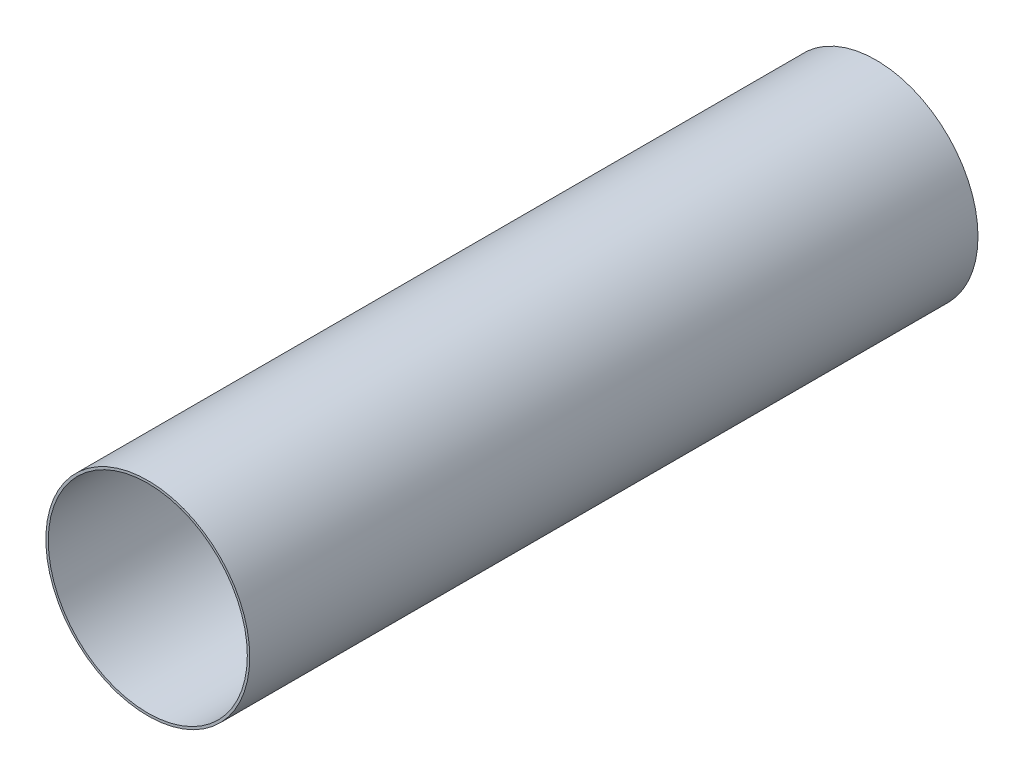
SolidWorks part; units mm, degrees
ref_plane "Alzado" through (0, 0, 0) normal (0, 0, 1) x (1, 0, 0)
ref_plane "Planta" through (0, 0, 0) normal (0, 1, 0) x (1, 0, 0)
ref_plane "Vista lateral" through (0, 0, 0) normal (1, 0, 0) x (0, 0, -1)
sketch "Croquis1" plane through (0, 0, 0) normal (0, 0, 1) x (1, 0, 0)
  circle A0 centre (0, 0) radius 2.05
  circle A1 centre (0, 0) radius 2.1
  dimension "D1" = 4.1
  dimension "D2" = 4.2
extrude "Saliente-Extruir1" add sketch "Croquis1" along normal blind 15 contours A1 A0
equation "\"k\"= 25.884"
equation "\"A_ALETA\"= ( ( ( tan ( \"ANG_ALETA\" ) ) * \"L_ALETA\" ) + \"A_BASE\" - ( \"GAP_ALETAS\" / 2 ) )"
equation "\"A_BASE\"= ( \"L_DIE\" - \"E_CAJA\" )"
equation "\"L_ALETA\"=90.000000"
equation "\"TAU_ALETA\"= ( \"L_ALETA\" / ( log ( ( \"A_ALETA\" ) + 1 ) ) )"
equation "\"E_ALETA\"=5.000000"
equation "\"R_SONDA\"= 2.05"
equation "\"D_SONDA\"=20.000000"
equation "\"L_CAJA\"=25.000000"
equation "\"E_CAJA\"= 2.5"
equation "\"A_CAJA\"= ( 2 * \"A_BASE\" ) + \"GAP_ALETAS\""
equation "\"W_CAJA\"= \"A_CAJA\" * \"CONST_CAJA\""
equation "\"W_CONC\"= ( \"W_CAJA\" / \"CONST_CONC\" ) "
equation "\"A_CONC\"= ( \"A_CAJA\" / \"CONST_CONC\" )"
equation "\"L_CONC\"= \"D_SONDA\" - \"OFFSET_CONC\""
equation "\"W_ALETA\"=70.000000"
equation "\"L_DIE_SONDA\"= ( \"GAP_ALETAS\" / 4 )"
equation "\"GAP_ALETAS\"=1.500000"
equation "\"D1@Croquis1\" = \"R_SONDA\" * 2"
equation "\"D1@Saliente-Extruir1\"  = \"L_DIE\""
equation "\"D2@Croquis1\" = 2 * \"R_SONDA\" + \"TOLERANCIA\""
equation "\"CONST_CONC\"=2.000000"
equation "\"K\"= 1.5"
equation "\"L_DIE\"= 15"
equation "\"L_CI\"= 18"
equation "\"CONST_CAJA\"=2.000000"
equation "\"ANG_ALETA\"=15.000000"
equation "\"R_C_SONDA\"= 0.63"
equation "\"TOLERANCIA\"= 0.1"
equation "\"OFFSET_CONC\"= ( 2 * \"R_TORNILLO\" )"
equation "\"R_TORNILLO\"=2.600000"
